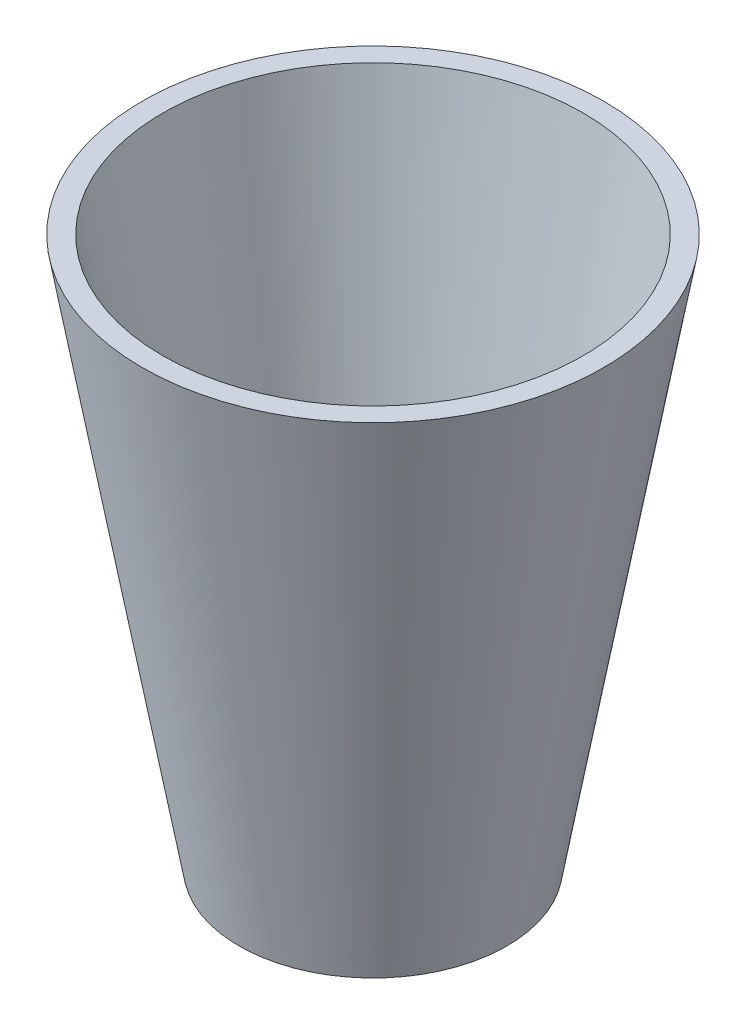
SolidWorks part; units mm, degrees
ref_plane "Alzado" through (0, 0, 0) normal (0, 0, 1) x (1, 0, 0)
ref_plane "Planta" through (0, 0, 0) normal (0, 1, 0) x (1, 0, 0)
ref_plane "Vista lateral" through (0, 0, 0) normal (1, 0, 0) x (0, 0, -1)
sketch "Croquis1" plane through (0, 0, 0) normal (1, 0, 0) x (0, 0, -1)
  line L0 (0, 0) -> (22.875, 0)
  line L1 (22.875, 0) -> (39.4, 93.8)
  line L2 (0, 0) -> (0, 34.42) construction
  line L3 (0, 3.45) -> (19.9797, 3.45)
  line L4 (19.9797, 3.45) -> (35.8969, 93.8)
  line L5 (19.9797, 3.45) -> (36.0023, 94.3986) construction
  line L6 (39.4, 93.8) -> (35.8969, 93.8)
  line L7 (0, 3.45) -> (0, 0)
  dimension "D1" = 22.875
  dimension "D2" = 39.4
  dimension "D3" = 93.8
  dimension "D4" = 3.45
revolve "Revolución1" add sketch "Croquis1" angle 360 about L2
equation "\"D1@Croquis1\"=45.75/2"
equation "\"D2@Croquis1\"=78.8/2"
